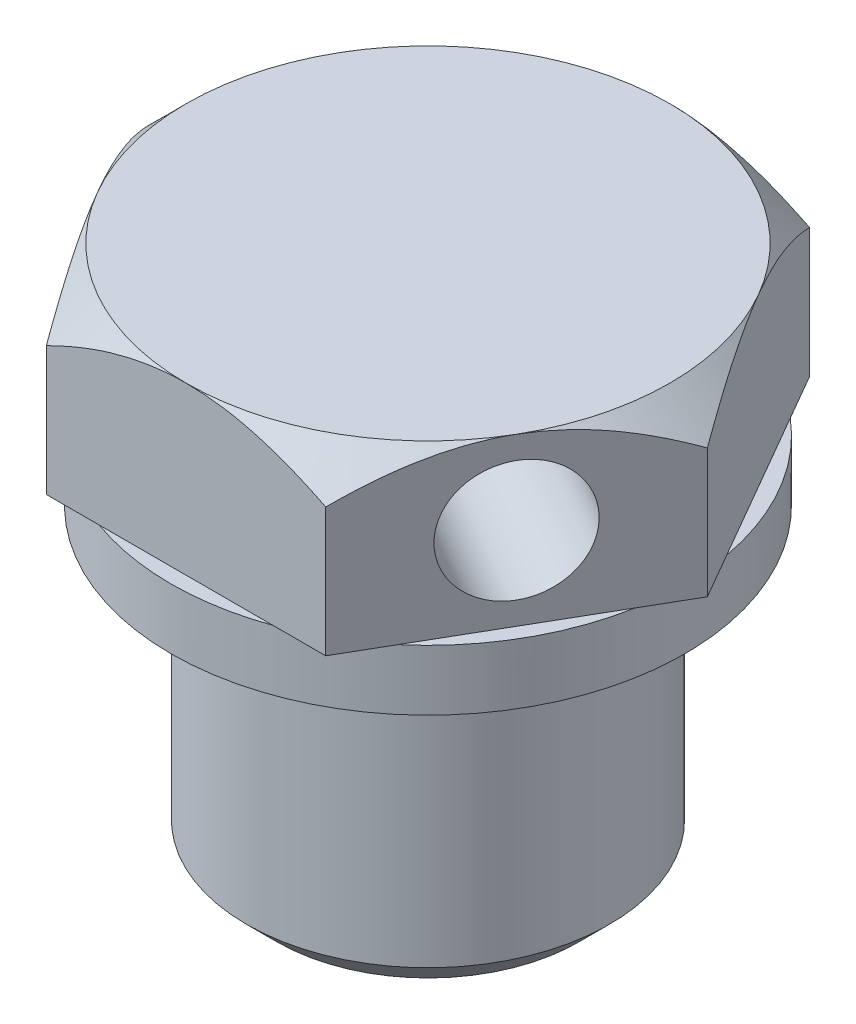
SolidWorks part; units mm, degrees
ref_plane "Front Plane" through (0, 0, 0) normal (0, 0, 1) x (1, 0, 0)
ref_plane "Top Plane" through (0, 0, 0) normal (0, 1, 0) x (1, 0, 0)
ref_plane "Right Plane" through (0, 0, 0) normal (1, 0, 0) x (0, 0, -1)
sketch "Sketch1" plane through (0, 0, 0) normal (0, 0, 1) x (1, 0, 0)
  line L0 (0, 0) -> (-5, 0)
  line L1 (-6, 1) -> (-6, 8.5)
  line L2 (-6, 10) -> (-8.5, 10)
  line L3 (-8.5, 10) -> (-8.5, 12)
  line L4 (-8.5, 12) -> (0, 12)
  line L5 (0, 12) -> (0, 0)
  line L6 (-5, 0) -> (-6, 1)
  line L7 (-6, 8.5) -> (0, 8.5) construction
  arc A0 (-6, 8.5) -> (-6, 10) centre (-6, 9.25) ccw
  point P1 (-6, 0)
  dimension "D3" = 1.5
  dimension "D1" = 6
  dimension "D2" = 10
  dimension "D4" = 2
  dimension "D5" = 8.5
revolve "Revolve1" add sketch "Sketch1" angle 360 about L5
sketch "Sketch2" plane through (0, 12, 0) normal (0, 1, 0) x (1, 0, 0)
  line L1 (-4.6188, 8) -> (-9.2376, 0)
  line L2 (-9.2376, 0) -> (-4.6188, -8)
  line L3 (-4.6188, -8) -> (4.6188, -8)
  line L4 (4.6188, -8) -> (9.2376, 0)
  line L5 (9.2376, 0) -> (4.6188, 8)
  line L6 (4.6188, 8) -> (-4.6188, 8)
  circle A0 centre (0, 0) radius 8 construction
  dimension "D1" = 16
extrude "Boss-Extrude1" add sketch "Sketch2" along normal blind 5.5
sketch "Sketch3" plane through (0, 17.5, 0) normal (0, 1, 0) x (1, 0, 0)
  line L0 (4.6188, 8) -> (-4.6188, 8) construction
  circle A0 centre (0, 0) radius 8
extrude "Cut-Extrude1" cut sketch "Sketch3" against normal blind 5.5 draft 45 flip side to cut
hole_wizard "Ø4.0mm Dowel Hole1" positions "Sketch4" profile "Sketch5" hole size "Ø4.0" standard "ISO"
sketch "Sketch4" plane through (0, 0, 0) normal (0, -1, 0) x (-1, 0, 0)
  point P0 (0, 0)
sketch "Sketch5" plane through (0, 0, 0) normal (1, 0, 0) x (0, 0, -1)
  line L0 (0, 0) -> (0, 17.2017)
  line L1 (0, 17.2017) -> (2, 16)
  line L2 (2, 16) -> (2, 0)
  line L5 (2, 0) -> (0, 0)
  line L10 (0, 17.2017) -> (-2, 16) construction
  line L11 (0, -6.35) -> (0, 107.95) construction
  dimension "Hole Dia." = 4
  dimension "Hole Depth" = 16
  dimension "Drill Angle" = 118
sketch "Sketch6" plane through (6.9282, 0, 4) normal (0.866, 0, 0.5) x (0.5, 0, -0.866)
  line L1 (0, 14.75) -> (0, 17.5) construction
  line L2 (0, 14.75) -> (0, 12) construction
  line L3 (-2.8723, 12) -> (2.8723, 12) construction
  circle A0 centre (0, 14.75) radius 2
  dimension "D2" = 4
extrude "Cut-Extrude2" cut sketch "Sketch6" against normal up to next
